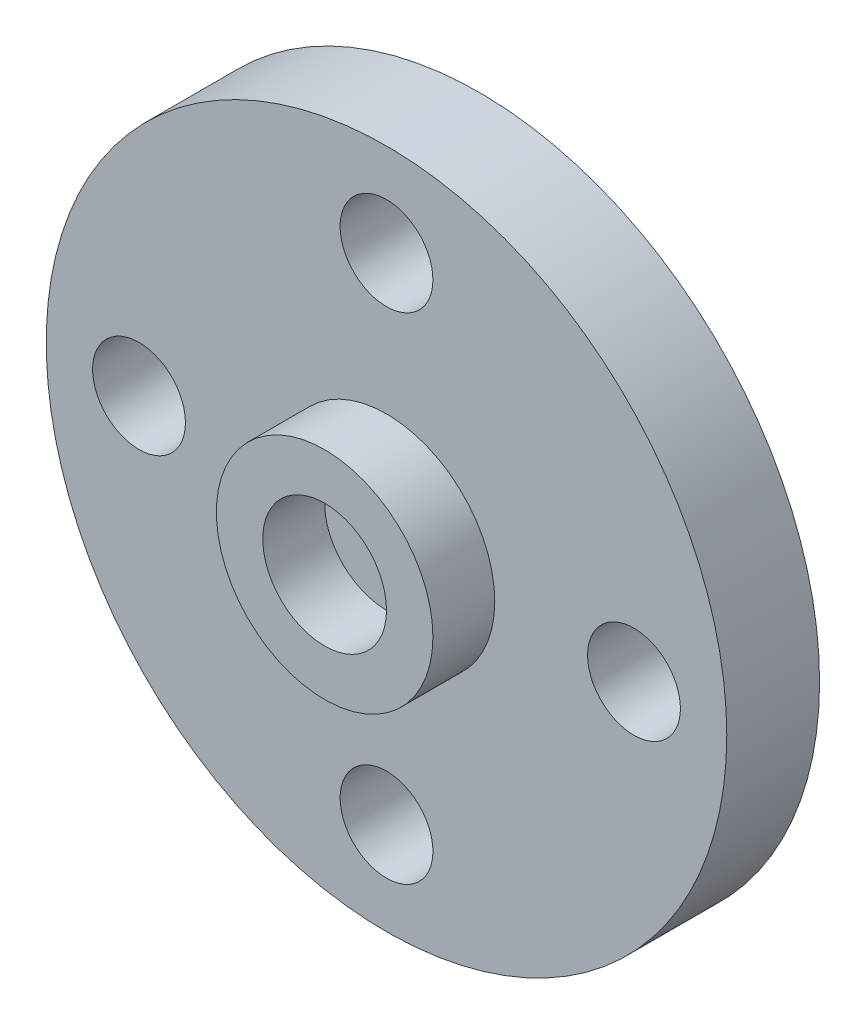
SolidWorks part; units mm, degrees
ref_plane "Front Plane" through (0, 0, 0) normal (0, 0, 1) x (1, 0, 0)
ref_plane "Top Plane" through (0, 0, 0) normal (0, 1, 0) x (1, 0, 0)
ref_plane "Right Plane" through (0, 0, 0) normal (1, 0, 0) x (0, 0, -1)
sketch "Sketch1" plane through (0, 0, 0) normal (0, 0, 1) x (1, 0, 0)
  circle A0 centre (0, 0) radius 11
  dimension "D1" = 22
extrude "Boss-Extrude1" add sketch "Sketch1" along normal blind 3
sketch "Sketch2" plane through (0, 0, 3) normal (0, 0, 1) x (1, 0, 0)
  line L0 (0, 0) -> (0, 8) construction
  line L1 (0, 0) -> (-8, 0) construction
  circle A0 centre (0, 8) radius 1.5
  circle A1 centre (-8, 0) radius 1.5
  circle A2 centre (0, -8) radius 1.5
  circle A3 centre (8, 0) radius 1.5
  dimension "D1" = 3
  dimension "D2" = 8
  dimension "D4" = 3
  dimension "D3" = 8
extrude "Cut-Extrude1" cut sketch "Sketch2" against normal blind 3
sketch "Sketch3" plane through (0, 0, 3) normal (0, 0, 1) x (1, 0, 0)
  circle A0 centre (0, 0) radius 3.5
  circle A1 centre (0, 0) radius 2
  dimension "D1" = 7
  dimension "D2" = 4
extrude "Boss-Extrude2" add sketch "Sketch3" along normal blind 2
